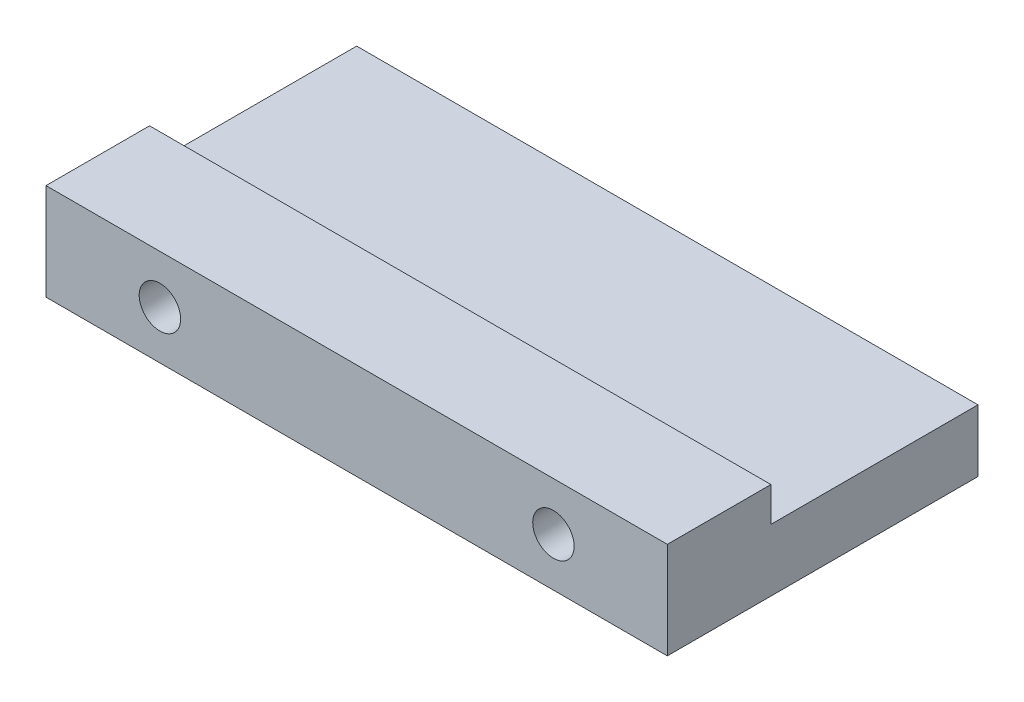
SolidWorks part; units mm, degrees
ref_plane "前视基准面" through (0, 0, 0) normal (0, 0, 1) x (1, 0, 0)
ref_plane "上视基准面" through (0, 0, 0) normal (0, 1, 0) x (1, 0, 0)
ref_plane "右视基准面" through (0, 0, 0) normal (1, 0, 0) x (0, 0, -1)
sketch "草图1" plane through (0, 0, 0) normal (0, 0, 1) x (1, 0, 0)
  line L1 (0, 0) -> (180, 0)
  line L2 (0, 0) -> (0, -28)
  line L3 (0, -28) -> (180, -28)
  line L4 (180, 0) -> (180, -28)
  dimension "D1" = 180
  dimension "D2" = 28
extrude "拉伸1" add sketch "草图1" along normal blind 90
sketch "草图2" plane through (0, 0, 90) normal (0, 0, 1) x (1, 0, 0)
  line L0 (180, 0) -> (0, 0) construction
  circle A0 centre (33, -14) radius 6
  circle A1 centre (147, -14) radius 6
  dimension "D1" = 14
  dimension "D2" = 14
extrude "切除-拉伸1" cut sketch "草图2" against normal blind 30
sketch "草图3" plane through (0, 0, 0) normal (0, 1, 0) x (1, 0, 0)
  line L0 (0, -90) -> (0, 0) construction
  line L1 (180, 0) -> (0, 0)
  line L2 (180, 0) -> (180, -60)
  line L3 (180, -60) -> (0, -60)
  line L4 (0, 0) -> (0, -60)
  dimension "D1" = 60
extrude "切除-拉伸2" cut sketch "草图3" against normal blind 10
